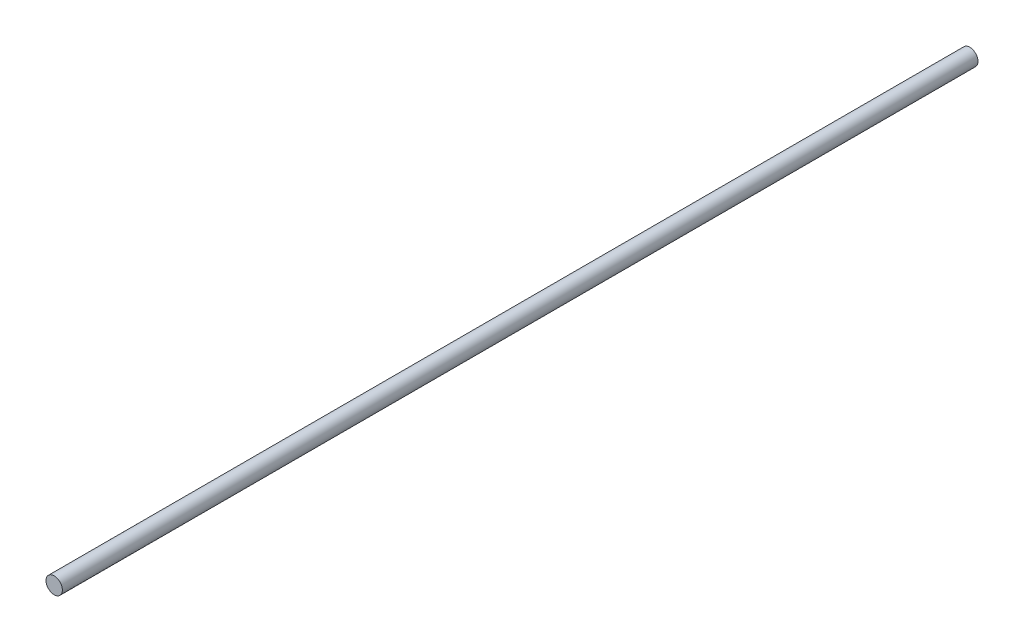
SolidWorks part; units mm, degrees
ref_plane "Front Plane" through (0, 0, 0) normal (0, 0, 1) x (1, 0, 0)
ref_plane "Top Plane" through (0, 0, 0) normal (0, 1, 0) x (1, 0, 0)
ref_plane "Right Plane" through (0, 0, 0) normal (1, 0, 0) x (0, 0, -1)
sketch "Sketch1" plane through (0, 0, 0) normal (0, 0, 1) x (1, 0, 0)
  circle A0 centre (0, 0) radius 4.75
  dimension "D1" = 9.5
extrude "Boss-Extrude1" add sketch "Sketch1" along normal blind 530
